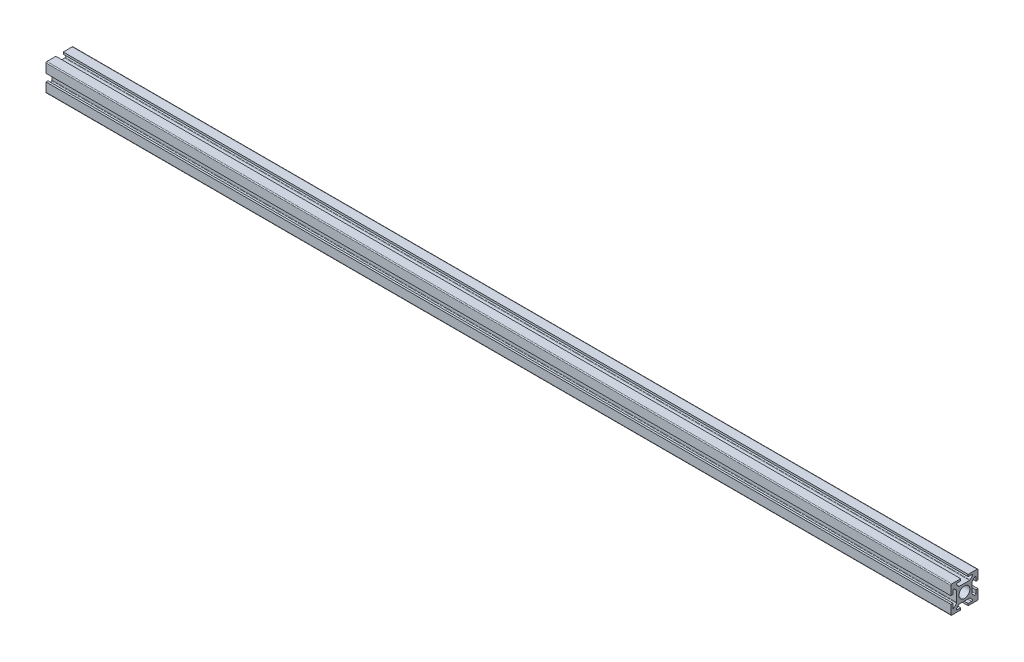
SolidWorks part; units mm, degrees
ref_plane "Front Plane" through (0, 0, 0) normal (0, 0, 1) x (1, 0, 0)
ref_plane "Top Plane" through (0, 0, 0) normal (0, 1, 0) x (1, 0, 0)
ref_plane "Right Plane" through (0, 0, 0) normal (1, 0, 0) x (0, 0, -1)
sketch "Sketch1" plane through (0, 0, 0) normal (1, 0, 0) x (0, 0, -1)
  line L3 (15, 15) -> (-15, 15) construction
  line L5 (15, -15) -> (-15, 15) construction
  line L6 (15, 15) -> (-15, -15) construction
  line L7 (-10.3, 12.8) -> (-6, 8.5)
  line L8 (-6, 8.5) -> (6, 8.5)
  line L9 (6, 8.5) -> (10.3, 12.8)
  line L10 (-10.3, 12.8) -> (-4.1, 12.8)
  line L11 (-4.1, 12.8) -> (-4.1, 15)
  line L12 (10.3, 12.8) -> (4.1, 12.8)
  line L13 (4.1, 12.8) -> (4.1, 15)
  line L14 (-4.1, 15) -> (-15, 15)
  line L15 (4.1, 15) -> (15, 15)
  line L16 (12.8, 10.3) -> (8.5, 6)
  line L17 (8.5, 6) -> (8.5, -6)
  line L18 (8.5, -6) -> (12.8, -10.3)
  line L19 (12.8, 10.3) -> (12.8, 4.1)
  line L20 (12.8, 4.1) -> (15, 4.1)
  line L21 (12.8, -10.3) -> (12.8, -4.1)
  line L22 (12.8, -4.1) -> (15, -4.1)
  line L23 (15, 4.1) -> (15, 15)
  line L24 (15, -4.1) -> (15, -15)
  line L25 (15, -15) -> (15, 15) construction
  line L26 (10.3, -12.8) -> (6, -8.5)
  line L27 (6, -8.5) -> (-6, -8.5)
  line L28 (-6, -8.5) -> (-10.3, -12.8)
  line L29 (10.3, -12.8) -> (4.1, -12.8)
  line L30 (4.1, -12.8) -> (4.1, -15)
  line L31 (-10.3, -12.8) -> (-4.1, -12.8)
  line L32 (-4.1, -12.8) -> (-4.1, -15)
  line L33 (4.1, -15) -> (15, -15)
  line L34 (-4.1, -15) -> (-15, -15)
  line L35 (-15, -15) -> (15, -15) construction
  line L36 (-12.8, -10.3) -> (-8.5, -6)
  line L37 (-8.5, -6) -> (-8.5, 6)
  line L38 (-8.5, 6) -> (-12.8, 10.3)
  line L39 (-12.8, -10.3) -> (-12.8, -4.1)
  line L40 (-12.8, -4.1) -> (-15, -4.1)
  line L41 (-12.8, 10.3) -> (-12.8, 4.1)
  line L42 (-12.8, 4.1) -> (-15, 4.1)
  line L43 (-15, -4.1) -> (-15, -15)
  line L44 (-15, 4.1) -> (-15, 15)
  line L45 (-15, 15) -> (-15, -15) construction
  circle A0 centre (0, 0) radius 6
  circle A1 centre (0, 0) radius 6
  circle A2 centre (0, 0) radius 6
  circle A3 centre (0, 0) radius 6
  point P0 (0, 0)
  point P9 (0, 8.5)
  point P53 (0, 0)
  dimension "D2" = 12
  dimension "D1" = 30
  dimension "D3" = 6.5
  dimension "D4" = 2.2
  dimension "D5" = 8.2
  dimension "D6" = 12
  dimension "D7" = 4
extrude "Boss-Extrude2" add sketch "Sketch1" along normal mid plane 1000 contours L44 L14 L11 L10 L7 L8 L9 L12 L13 L15 L23 L20 L19 L16 L17 L18 L21 L22 L24 L33 L30 L29 L26 L27 L28 L31 L32 L34 L43 L40 L39 L36 L37 L38 L41 L42
fillet "Fillet1" radius 1 18 edges at (0, 15, 15) (0, -6, -8.5) (0, 6, -8.5) (0, 10.3, -12.8) (0, -12.8, 10.3) (0, -12.8, -10.3) (0, -10.3, -12.8) (0, -15, -15) (0, -15, 15) (0, -6, 8.5) (0, -8.5, -6) (0, 6, 8.5) (0, 10.3, 12.8) (0, 15, -15) (0, 12.8, -10.3) (0, 8.5, -6) (0, 8.5, 6) (0, 12.8, 10.3)
sketch "Sketch2" plane through (-500, 0, 0) normal (-1, 0, 0) x (0, 0, 1)
  circle A0 centre (0, 0) radius 6
  dimension "D1" = 12
extrude "Cut-Extrude1" cut sketch "Sketch2" against normal through all
